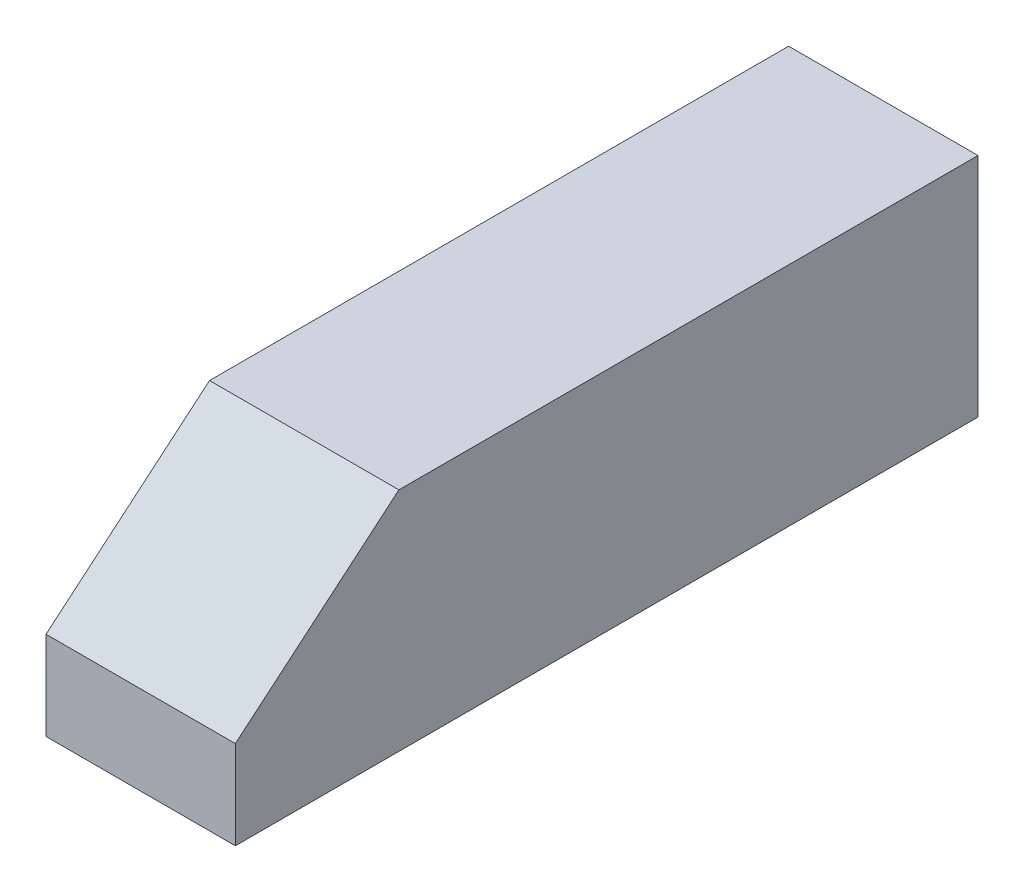
SolidWorks part; units mm, degrees
ref_plane "Front Plane" through (0, 0, 0) normal (0, 0, 1) x (1, 0, 0)
ref_plane "Top Plane" through (0, 0, 0) normal (0, 1, 0) x (1, 0, 0)
ref_plane "Right Plane" through (0, 0, 0) normal (1, 0, 0) x (0, 0, -1)
sketch "Sketch1" plane through (0, 0, 0) normal (0, 0, 1) x (1, 0, 0)
  line L1 (-9.3356, 7.0017) -> (0.8644, 7.0017)
  line L2 (-9.3356, 7.0017) -> (-9.3356, -5.1983)
  line L3 (-9.3356, -5.1983) -> (0.8644, -5.1983)
  line L4 (0.8644, 7.0017) -> (0.8644, -5.1983)
  dimension "D1" = 10.2
  dimension "D2" = 12.2
extrude "Boss-Extrude1" add sketch "Sketch1" along normal blind 40
ref_plane "Plane1" through (0.8644, 0, 0) normal (1, 0, 0) x (0, 0, -1)
sketch "Sketch2" plane through (0.8644, 0, 0) normal (1, 0, 0) x (0, 0, -1)
  line L0 (-40, -0.4292) -> (-31.192, 7.0017)
  line L1 (-40, -5.1983) -> (-40, 7.0017) construction
  line L2 (-40, 7.0017) -> (0, 7.0017) construction
  line L3 (-31.192, 7.0017) -> (-40, 7.0017)
  line L5 (-40, -0.4292) -> (-40, 7.0017)
extrude "Cut-Extrude1" cut sketch "Sketch2" against normal blind 50
